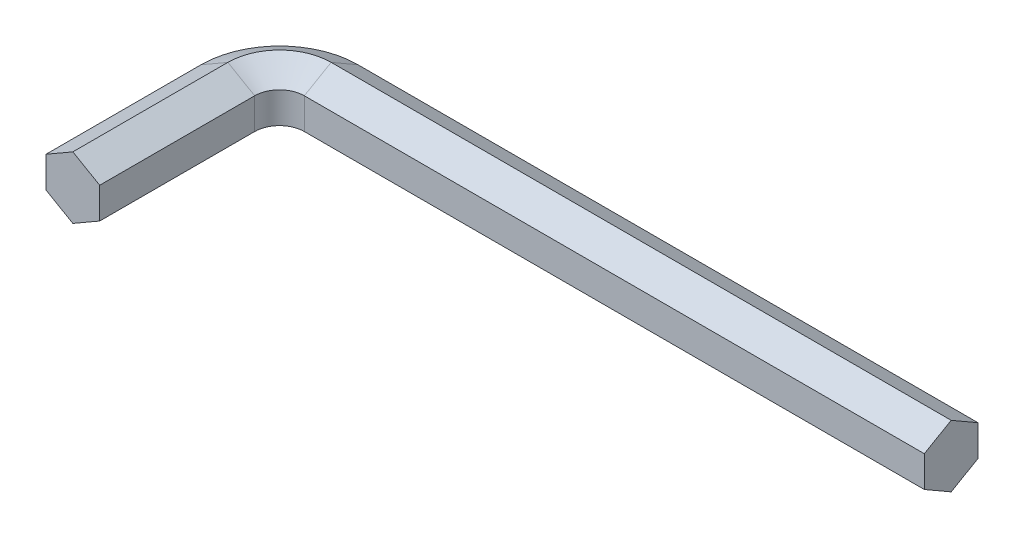
SolidWorks part; units mm, degrees
ref_plane "Front Plane" through (0, 0, 0) normal (0, 0, 1) x (1, 0, 0)
ref_plane "Top Plane" through (0, 0, 0) normal (0, 1, 0) x (1, 0, 0)
ref_plane "Right Plane" through (0, 0, 0) normal (1, 0, 0) x (0, 0, -1)
sketch "Sketch1" plane through (0, 0, 0) normal (0, 1, 0) x (1, 0, 0)
  line L0 (-9.4872, -11.7949) -> (-9.4872, 3.2051)
  line L1 (-4.4872, 8.2051) -> (55.5128, 8.2051)
  arc A0 (-9.4872, 3.2051) -> (-4.4872, 8.2051) centre (-4.4872, 3.2051) cw
  dimension "D1" = 5
  dimension "D2" = 15
  dimension "D3" = 60
ref_plane "Plane1" through (55.5128, 0, 0) normal (1, 0, 0) x (0, 0, -1)
sketch "Sketch2" plane through (55.5128, 0, 0) normal (1, 0, 0) x (0, 0, -1)
  line L0 (8.2051, 0) -> (3.2051, 0) construction
  line L1 (5.6071, 1.5) -> (5.6071, -1.5)
  line L2 (5.6071, -1.5) -> (8.2051, -3)
  line L3 (8.2051, -3) -> (10.8032, -1.5)
  line L4 (10.8032, -1.5) -> (10.8032, 1.5)
  line L5 (10.8032, 1.5) -> (8.2051, 3)
  line L6 (8.2051, 3) -> (5.6071, 1.5)
  circle A0 centre (8.2051, 0) radius 2.5981 construction
  dimension "D1" = 3
sweep "Sweep1" add profiles "Sketch2" path "Sketch1"
